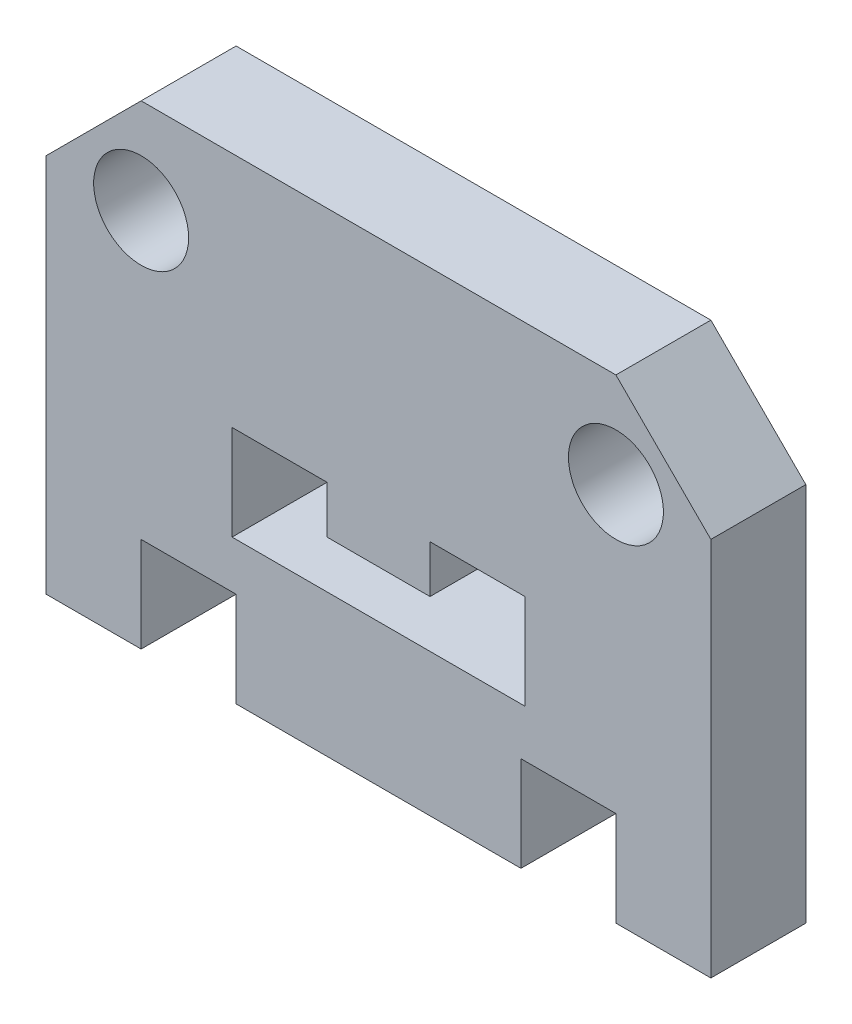
SolidWorks part; units mm, degrees
ref_plane "Front Plane" through (0, 0, 0) normal (0, 0, 1) x (1, 0, 0)
ref_plane "Top Plane" through (0, 0, 0) normal (0, 1, 0) x (1, 0, 0)
ref_plane "Right Plane" through (0, 0, 0) normal (1, 0, 0) x (0, 0, -1)
sketch "Sketch1" plane through (0, 0, 0) normal (0, 0, 1) x (1, 0, 0)
  line L0 (0, 11.7108) -> (0, -47.4217) construction
  line L1 (25, 12.1446) -> (-25, 12.1446)
  line L2 (-25, 12.1446) -> (-35, 2.1446)
  line L3 (-35, 2.1446) -> (-35, -37.8554)
  line L4 (-35, -37.8554) -> (-25, -37.8554)
  line L5 (-25, -37.8554) -> (-25, -27.8554)
  line L6 (-25, -27.8554) -> (-15, -27.8554)
  line L7 (-15, -27.8554) -> (-15, -37.8554)
  line L8 (-15, -37.8554) -> (15, -37.8554)
  line L9 (5.4217, -17.8554) -> (-5.4217, -17.8554)
  line L10 (-5.4217, -17.8554) -> (-5.4217, -12.8554)
  line L11 (-5.4217, -12.8554) -> (-15.4217, -12.8554)
  line L12 (-15.4217, -12.8554) -> (-15.4217, -22.8554)
  line L13 (-15.4217, -22.8554) -> (15.4217, -22.8554)
  line L14 (15, -27.8554) -> (15, -37.8554)
  line L15 (25, -27.8554) -> (15, -27.8554)
  line L16 (25, -37.8554) -> (25, -27.8554)
  line L17 (35, -37.8554) -> (25, -37.8554)
  line L18 (5.4217, -17.8554) -> (5.4217, -12.8554)
  line L19 (15.4217, -12.8554) -> (15.4217, -22.8554)
  line L20 (5.4217, -12.8554) -> (15.4217, -12.8554)
  line L21 (35, 2.1446) -> (35, -37.8554)
  line L22 (25, 12.1446) -> (35, 2.1446)
  line L23 (54.1687, -37.8554) -> (-73.0602, -37.8554) construction
  circle A0 centre (-25, 2.1446) radius 5
  circle A1 centre (25, 2.1446) radius 5
  point P22 (0, -37.8554)
  point P27 (0, -22.8554)
  point P28 (0, -17.8554)
  point P34 (0, 12.1446)
  dimension "D11" = 10
  dimension "D1" = 40
  dimension "D2" = 10
  dimension "D3" = 10
  dimension "D4" = 10
  dimension "D5" = 10
  dimension "D6" = 15
  dimension "D7" = 10
  dimension "D8" = 5.4217
  dimension "D9" = 10
  dimension "D10" = 5
  dimension "D12" = 10
  dimension "D13" = 15
  dimension "D14" = 10
extrude "Boss-Extrude2" add sketch "Sketch1" along normal blind 10
